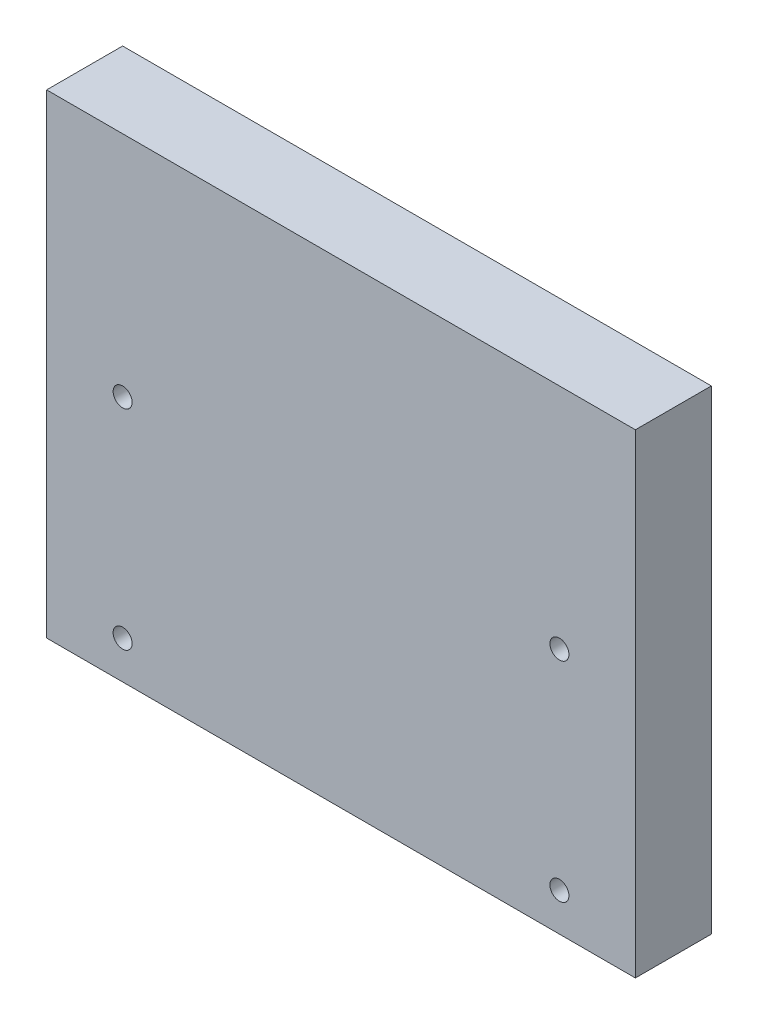
SolidWorks part; units mm, degrees
ref_plane "Plan de face" through (0, 0, 0) normal (0, 0, 1) x (1, 0, 0)
ref_plane "Plan de dessus" through (0, 0, 0) normal (0, 1, 0) x (1, 0, 0)
ref_plane "Plan de droite" through (0, 0, 0) normal (1, 0, 0) x (0, 0, -1)
sketch "Esquisse1" plane through (0, 0, 0) normal (0, 0, 1) x (1, 0, 0)
  line L0 (7.6098, -32.6444) -> (7.6098, 6.8885) construction
  line L1 (-23.3902, 24.7758) -> (38.6098, 24.7758)
  line L2 (-23.3902, 24.7758) -> (-23.3902, -25.2242)
  line L3 (-23.3902, -25.2242) -> (38.6098, -25.2242)
  line L4 (38.6098, 24.7758) -> (38.6098, -25.2242)
  line L5 (42.9739, -10.2242) -> (-3.3888, -10.2242) construction
  line L6 (-15.3902, -32.6444) -> (-15.3902, -15.3688) construction
  line L7 (42.9739, -21.2242) -> (-14.5576, -21.2242) construction
  circle A0 centre (-15.3902, -21.2242) radius 1
  circle A1 centre (30.6098, -21.2242) radius 1
  circle A2 centre (-15.3902, 0.7758) radius 1
  circle A3 centre (30.6098, 0.7758) radius 1
  dimension "D4" = 31
  dimension "D1" = 11
  dimension "D2" = 23
  dimension "D3" = 4
extrude "Boss.-Extru.1" add sketch "Esquisse1" along normal blind 8
